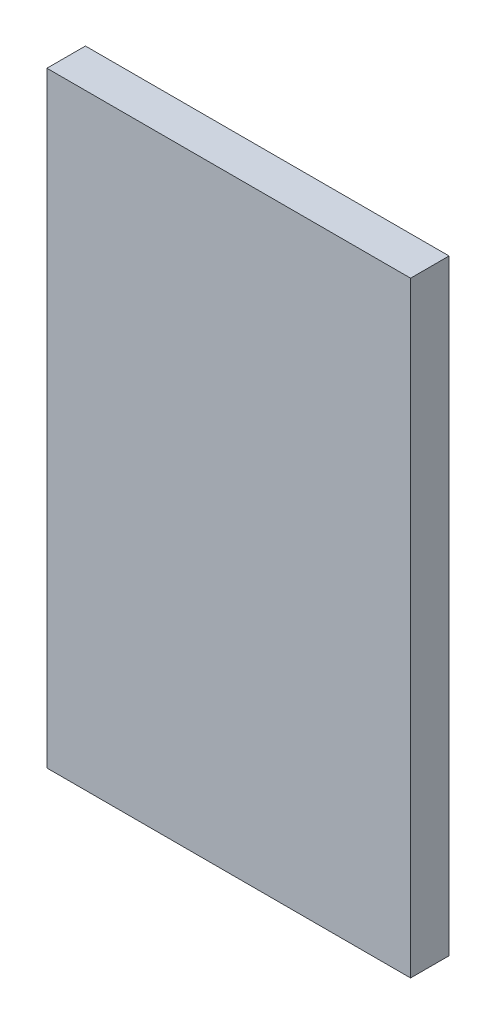
SolidWorks part; units mm, degrees
ref_plane "Front Plane" through (0, 0, 0) normal (0, 0, 1) x (1, 0, 0)
ref_plane "Top Plane" through (0, 0, 0) normal (0, 1, 0) x (1, 0, 0)
ref_plane "Right Plane" through (0, 0, 0) normal (1, 0, 0) x (0, 0, -1)
sketch "Sketch1" plane through (0, 0, 0) normal (0, 0, 1) x (1, 0, 0)
  line L1 (0, 0) -> (60, 0)
  line L2 (0, 0) -> (0, 100)
  line L3 (0, 100) -> (60, 100)
  line L4 (60, 0) -> (60, 100)
  dimension "D1" = 60
  dimension "D2" = 100
extrude "Boss-Extrude1" add sketch "Sketch1" along normal blind 6.35
